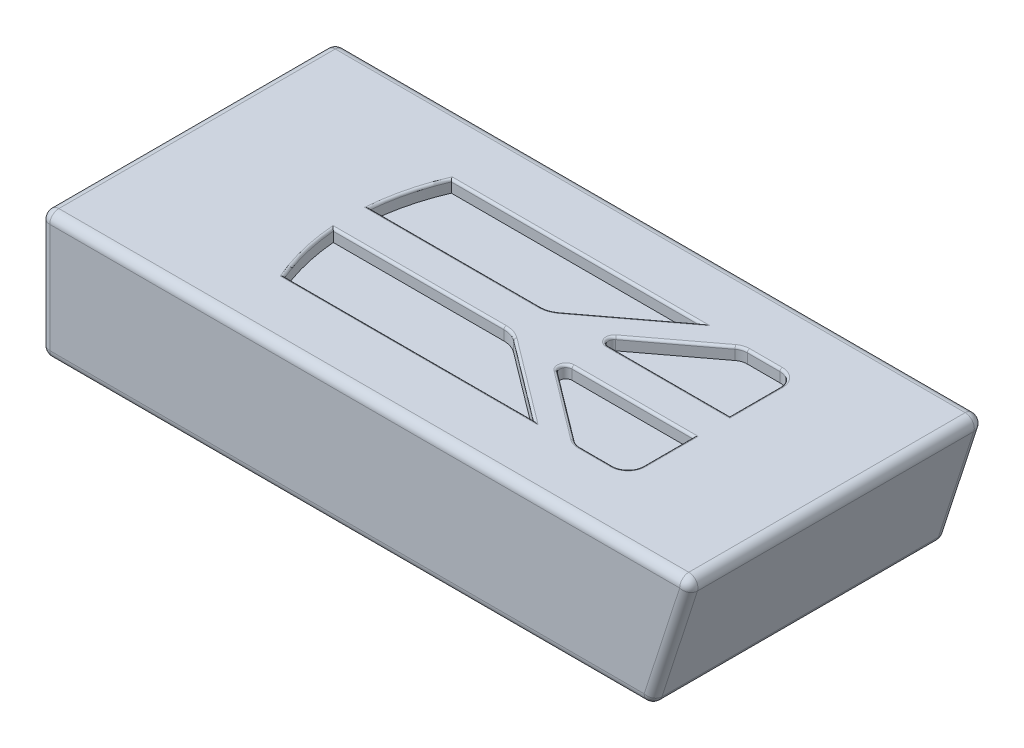
SolidWorks part; units mm, degrees
ref_plane "Front Plane" through (0, 0, 0) normal (0, 0, 1) x (1, 0, 0)
ref_plane "Top Plane" through (0, 0, 0) normal (0, 1, 0) x (1, 0, 0)
ref_plane "Right Plane" through (0, 0, 0) normal (1, 0, 0) x (0, 0, -1)
sketch "Sketch1" plane through (0, 0, 0) normal (0, 0, 1) x (1, 0, 0)
  line L0 (0, 0) -> (49.022, 0)
  line L1 (0, 0) -> (0, 8.382)
  line L2 (0, 8.382) -> (49.022, 8.382)
  line L3 (49.022, 8.382) -> (49.022, 0)
  dimension "D1" = 49.022
  dimension "D2" = 8.382
extrude "Boss-Extrude1" add sketch "Sketch1" along normal mid plane 22.352
fillet "Fillet1" radius 0.508 12 edges at (49.022, 4.191, -11.176) (49.022, 4.191, 11.176) (0, 4.191, 11.176) (0, 4.191, -11.176) (0, 0, 0) (24.511, 0, 11.176) (49.022, 0, 0) (24.511, 0, -11.176) (49.022, 8.382, 0) (24.511, 8.382, 11.176) (0, 8.382, 0) (24.511, 8.382, -11.176)
sketch "Sketch2" plane through (0, 0, 0) normal (0, 0, 1) x (1, 0, 0)
  line L0 (-0.127, -0.127) -> (-0.127, 8.509)
  line L1 (-0.127, 8.509) -> (51.955, 8.509)
  line L2 (49.022, 7.874) -> (49.022, 0.508) construction
  line L3 (49.149, -0.127) -> (-0.127, -0.127)
  line L4 (0, 0.508) -> (0, 7.874) construction
  line L5 (0.508, 8.382) -> (48.514, 8.382) construction
  line L7 (48.514, 0) -> (0.508, 0) construction
  line L8 (49.149, -0.127) -> (51.955, 8.509)
  line L9 (-1.143, 9.525) -> (53.3534, 9.525)
  line L10 (49.8872, -1.143) -> (53.3534, 9.525)
  line L11 (49.8872, -1.143) -> (-1.143, -1.143)
  line L12 (-1.143, -1.143) -> (-1.143, 9.525)
  dimension "D1" = 0.127
  dimension "D2" = 0.127
  dimension "D3" = 0.127
  dimension "D4" = 0.127
  dimension "D5" = 18
  dimension "D6" = 1.016
extrude "Boss-Extrude2" add sketch "Sketch2" along normal mid plane 24.638 separate body
sketch "Sketch3" plane through (0, 0, 12.319) normal (0, 0, 1) x (1, 0, 0)
  line L0 (51.955, 8.509) -> (-0.127, 8.509) construction
  line L1 (-0.127, 8.509) -> (-0.127, -0.127) construction
  line L2 (-0.127, -0.127) -> (49.149, -0.127) construction
  line L3 (49.149, -0.127) -> (51.955, 8.509) construction
  line L4 (51.955, 8.509) -> (-0.127, 8.509)
  line L5 (-0.127, 8.509) -> (-0.127, -0.127)
  line L6 (-0.127, -0.127) -> (49.149, -0.127)
  line L7 (49.149, -0.127) -> (51.955, 8.509)
extrude "Boss-Extrude3" add sketch "Sketch3" against normal blind 1.016
sketch "Sketch4" plane through (0, 0, -12.319) normal (0, 0, -1) x (-1, 0, 0)
  line L0 (-51.955, 8.509) -> (0.127, 8.509) construction
  line L1 (-49.149, -0.127) -> (-51.955, 8.509) construction
  line L2 (0.127, -0.127) -> (-49.149, -0.127) construction
  line L3 (0.127, 8.509) -> (0.127, -0.127) construction
  line L4 (-51.955, 8.509) -> (0.127, 8.509)
  line L5 (-49.149, -0.127) -> (-51.955, 8.509)
  line L6 (0.127, -0.127) -> (-49.149, -0.127)
  line L7 (0.127, 8.509) -> (0.127, -0.127)
extrude "Boss-Extrude4" add sketch "Sketch4" against normal blind 1.016
fillet "Fillet2" radius 0.762 13 edges at (53.3534, 9.525, 0) (-1.143, 9.525, 0) (-1.143, -1.143, 0) (49.8872, -1.143, 0) (24.3721, -1.143, -12.319) (51.6203, 4.191, -12.319) (26.1052, 9.525, -12.319) (-1.143, 4.191, -12.319) (26.1052, 9.525, 12.319) (51.6203, 4.191, 12.319) (24.3721, -1.143, 12.319) (-1.143, 4.191, 12.319) (-0.127, 8.509, 0)
sketch "Sketch7" plane through (-1.143, 0, 0) normal (-1, 0, 0) x (0, 0, 1)
  line L0 (-11.557, 4.826) -> (11.557, 4.826) construction
  line L1 (-7.4676, 5.207) -> (-3.81, 5.207)
  line L2 (-7.4676, 5.207) -> (-7.4676, 4.445)
  line L3 (-7.4676, 4.445) -> (-3.81, 4.445)
  line L4 (-3.81, 5.207) -> (-3.81, 4.445)
  line L5 (3.81, 5.207) -> (7.4676, 5.207)
  line L6 (3.81, 5.207) -> (3.81, 4.445)
  line L7 (3.81, 4.445) -> (7.4676, 4.445)
  line L8 (7.4676, 5.207) -> (7.4676, 4.445)
  line L9 (-11.557, 8.763) -> (-11.557, -0.381) construction
  line L10 (11.557, -0.381) -> (11.557, 8.763) construction
  line L11 (0, 8.763) -> (0, -0.381) construction
  line L12 (11.557, 8.763) -> (-11.557, 8.763) construction
  line L13 (-11.557, -0.381) -> (11.557, -0.381) construction
  line L14 (11.557, -1.143) -> (-11.557, -1.143) construction
  point P14 (7.4676, 4.826)
  point P15 (-3.81, 4.826)
  dimension "D1" = 3.6576
  dimension "D2" = 0.762
  dimension "D3" = 5.969
  dimension "D4" = 7.62
extrude "Cut-Extrude2" cut sketch "Sketch7" against normal blind 8.89
fillet "Fillet3" radius 0.0762 8 edges at (-1.143, 5.207, 5.6388) (-1.143, 4.445, 5.6388) (-1.143, 4.826, 7.4676) (-1.143, 4.826, 3.81) (-1.143, 4.826, -3.81) (-1.143, 4.445, -5.6388) (-1.143, 4.826, -7.4676) (-1.143, 5.207, -5.6388)
sketch "Sketch8" plane through (0, 9.525, 0) normal (0, 1, 0) x (1, 0, 0)
  line L0 (-1.143, 0) -> (53.0666, 0) construction
  line L1 (-1.143, -11.557) -> (-1.143, 11.557) construction
  line L2 (53.0666, -11.557) -> (53.0666, 11.557) construction
  line L3 (13.8998, 6.985) -> (42.6526, 6.985)
  line L4 (42.6526, 6.985) -> (42.6526, -6.985)
  line L5 (42.6526, -6.985) -> (13.8998, -6.985)
  line L6 (52.3046, -11.557) -> (52.3046, 11.557) construction
  line L7 (12.5357, 1.524) -> (26.8009, 1.524)
  line L8 (28.0238, 1.9332) -> (34.7278, 6.985)
  line L9 (34.7278, 6.985) -> (38.233, 6.985)
  line L10 (38.233, 6.985) -> (32.1985, 2.4377)
  line L11 (32.5043, 1.524) -> (42.6526, 1.524)
  line L12 (42.6526, 1.524) -> (42.6526, -1.524)
  line L13 (34.7278, 6.985) -> (38.233, 6.985)
  line L14 (34.7278, -6.985) -> (38.233, -6.985)
  line L15 (32.5043, -1.524) -> (42.6526, -1.524)
  line L16 (38.233, -6.985) -> (32.1985, -2.4377)
  line L17 (34.7278, -6.985) -> (38.233, -6.985)
  line L18 (28.0238, -1.9332) -> (34.7278, -6.985)
  line L19 (12.5357, -1.524) -> (26.8009, -1.524)
  line L20 (13.8998, -6.985) -> (42.6526, -6.985)
  arc A0 (13.8998, 6.985) -> (13.8998, -6.985) centre (30.2503, 0) ccw
  arc A1 (32.5043, 1.524) -> (32.1985, 2.4377) centre (32.5043, 2.032) cw
  arc A2 (26.8009, 1.524) -> (28.0238, 1.9332) centre (26.8009, 3.556) ccw
  arc A3 (26.8009, -1.524) -> (28.0238, -1.9332) centre (26.8009, -3.556) cw
  arc A4 (32.5043, -1.524) -> (32.1985, -2.4377) centre (32.5043, -2.032) ccw
  point P12 (42.6526, 0)
  point P35 (42.6526, 0)
  dimension "D1" = 17.78
  dimension "D7" = 0.508
  dimension "D8" = 2.032
  dimension "D2" = 9.652
  dimension "D3" = 13.97
  dimension "D4" = 28.7528
  dimension "D5" = 1.524
  dimension "D6" = 37
  dimension "D9" = 20.828
  dimension "D10" = 3.5052
extrude "Cut-Extrude3" cut sketch "Sketch8" against normal up to next (1.016 mm away) contours L7 A2 L8 L3 A0 | A3 L19 A0 L5 L18 | A1 L11 L4 L3 L10 | L15 A4 L16 L5 L4
fillet "Fillet5" radius 1.27 4 edges at (38.233, 9.017, -6.985) (38.233, 9.017, 6.985) (42.6526, 9.017, 6.985) (42.6526, 9.017, -6.985)
fillet "Fillet6" radius 0.2032 24 edges at (32.0225, 9.525, 1.8708) (35.0461, 9.525, 4.5835) (38.255, 9.525, 6.9194) (40.0203, 9.525, 6.985) (42.2806, 9.525, 6.613) (42.6526, 9.525, 3.6195) (37.5784, 9.525, 1.524) (19.6683, 9.525, 1.524) (13.0003, 9.525, 4.3088) (24.3138, 9.525, 6.985) (31.3758, 9.525, 4.4591) (27.4457, 9.525, 1.629) (31.3758, 9.525, -4.4591) (24.3138, 9.525, -6.985) (13.0003, 9.525, -4.3088) (19.6683, 9.525, -1.524) (27.4457, 9.525, -1.629) (37.5784, 9.525, -1.524) (42.6526, 9.525, -3.6195) (42.2806, 9.525, -6.613) (40.0203, 9.525, -6.985) (38.255, 9.525, -6.9194) (35.0461, 9.525, -4.5835) (32.0225, 9.525, -1.8708)
ref_plane "Plane1" through (0, 4.191, 0) normal (0, 1, 0) x (1, 0, 0)
mirror "Mirror3" about plane through (0, 4.191, 0) normal (0, 1, 0) of "Cut-Extrude3"
fillet "Fillet7" radius 1.27 4 edges at (38.233, -0.635, 6.985) (42.6526, -0.635, 6.985) (38.233, -0.635, -6.985) (42.6526, -0.635, -6.985)
fillet "Fillet8" radius 0.2032 24 edges at (42.2806, -1.143, -6.613) (42.6526, -1.143, -3.6195) (37.5784, -1.143, -1.524) (32.0225, -1.143, -1.8708) (35.0461, -1.143, -4.5835) (38.255, -1.143, -6.9194) (40.0203, -1.143, -6.985) (13.0003, -1.143, 4.3088) (19.6683, -1.143, 1.524) (27.4457, -1.143, 1.629) (31.3758, -1.143, 4.4591) (24.3138, -1.143, 6.985) (19.6683, -1.143, -1.524) (13.0003, -1.143, -4.3088) (24.3138, -1.143, -6.985) (31.3758, -1.143, -4.4591) (27.4457, -1.143, -1.629) (38.255, -1.143, 6.9194) (35.0461, -1.143, 4.5835) (32.0225, -1.143, 1.8708) (37.5784, -1.143, 1.524) (42.6526, -1.143, 3.6195) (42.2806, -1.143, 6.613) (40.0203, -1.143, 6.985)
equation "\"D2@Sketch2\"=\"D1@Sketch2\""
equation "\"D3@Sketch2\"=\"D2@Sketch2\""
equation "\"D4@Sketch2\"=\"D3@Sketch2\""
